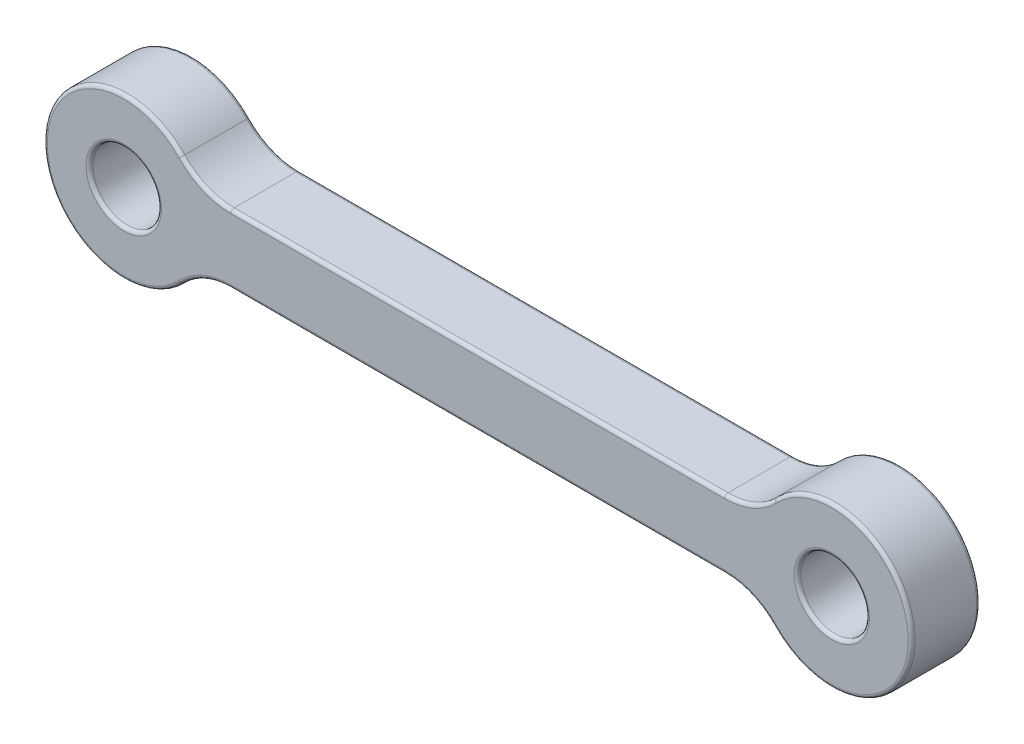
SolidWorks part; units mm, degrees
ref_plane "Front Plane" through (0, 0, 0) normal (0, 0, 1) x (1, 0, 0)
ref_plane "Top Plane" through (0, 0, 0) normal (0, 1, 0) x (1, 0, 0)
ref_plane "Right Plane" through (0, 0, 0) normal (1, 0, 0) x (0, 0, -1)
sketch "Sketch1" plane through (0, 0, 0) normal (0, 0, 1) x (1, 0, 0)
  line L0 (0, 0) -> (31, 0) construction
  line L1 (0, 3.5) -> (31, 3.5) construction
  line L2 (0, -3.5) -> (31, -3.5) construction
  line L3 (15.5, 0) -> (15.5, -3.5) construction
  line L5 (27.8377, -1.5) -> (3.1623, -1.5)
  line L6 (27.8377, -1.5) -> (27.8377, 1.5) construction
  line L7 (27.8377, 1.5) -> (3.1623, 1.5)
  line L8 (3.1623, -1.5) -> (3.1623, 1.5) construction
  line L9 (27.8377, -1.5) -> (3.1623, 1.5) construction
  line L10 (27.8377, 1.5) -> (3.1623, -1.5) construction
  arc A0 (0, 3.5) -> (0, -3.5) centre (0, 0) ccw construction
  arc A1 (31, -3.5) -> (31, 3.5) centre (31, 0) ccw construction
  circle A2 centre (0, 0) radius 3.5
  circle A3 centre (0, 0) radius 1.5
  circle A4 centre (31, 0) radius 1.5
  circle A5 centre (31, 0) radius 3.5
  point P3 (15.5, 0)
  dimension "D3" = 3
  dimension "D1" = 31
  dimension "D2" = 7
  dimension "D4" = 3
extrude "Boss-Extrude1" add sketch "Sketch1" along normal mid plane 3 contours A2 A3 | L5 A5 L7 A2 | A5 A4
fillet "Fillet1" radius 3 4 edges at (3.1623, 1.5, 0) (27.8377, 1.5, 0) (3.1623, -1.5, 0) (27.8377, -1.5, 0)
fillet "Fillet2" radius 0.15 20 edges at (32.5, 0, 1.5) (32.5, 0, -1.5) (27.4863, 1.7404, 1.5) (27.4863, 1.7404, -1.5) (34.5, 0, -1.5) (34.5, 0, 1.5) (27.4863, -1.7404, 1.5) (27.4863, -1.7404, -1.5) (15.5, -1.5, 1.5) (15.5, -1.5, -1.5) (3.5137, -1.7404, 1.5) (3.5137, -1.7404, -1.5) (-3.5, 0, 1.5) (-3.5, 0, -1.5) (3.5137, 1.7404, 1.5) (3.5137, 1.7404, -1.5) (15.5, 1.5, -1.5) (15.5, 1.5, 1.5) (1.5, 0, 1.5) (1.5, 0, -1.5)
